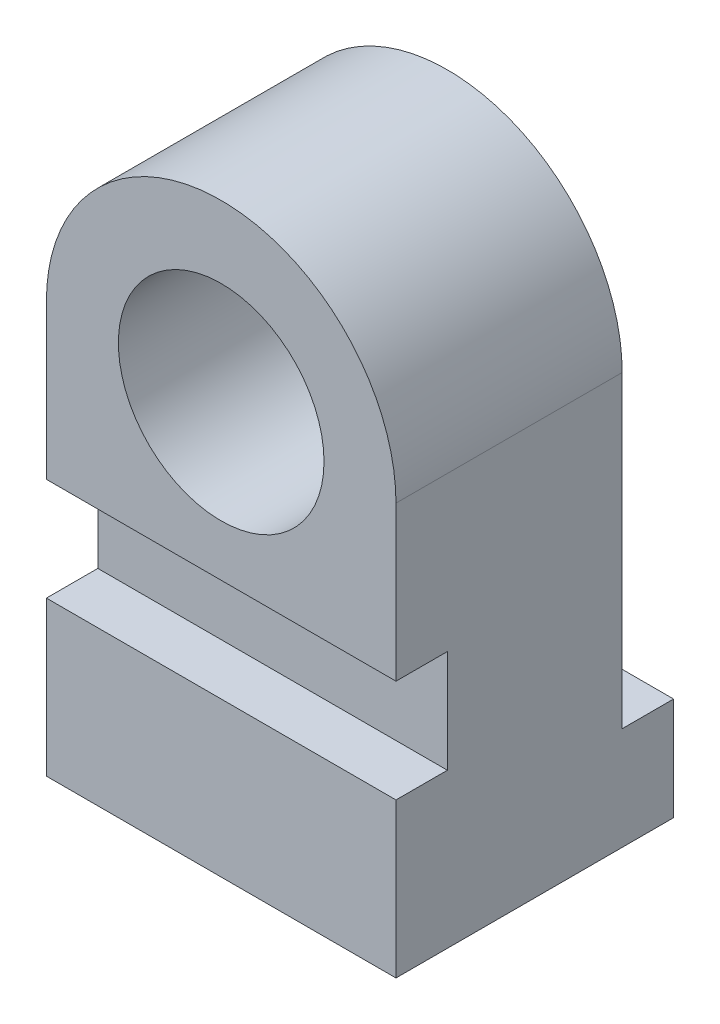
SolidWorks part; units mm, degrees
ref_plane "Front Plane" through (0, 0, 0) normal (0, 0, 1) x (1, 0, 0)
ref_plane "Top Plane" through (0, 0, 0) normal (0, 1, 0) x (1, 0, 0)
ref_plane "Right Plane" through (0, 0, 0) normal (1, 0, 0) x (0, 0, -1)
sketch "Sketch1" plane through (0, 0, 0) normal (0, 0, 1) x (1, 0, 0)
  line L0 (-17000, 0) -> (17000, 0)
  line L1 (0, 0) -> (0, 40000) construction
  line L2 (-24995.5692, 40000) -> (34311.1506, 40000) construction
  line L3 (-17000, 40000) -> (-17000, 0)
  line L4 (17000, 40000) -> (17000, 0)
  circle A0 centre (0, 40000) radius 10000
  arc A1 (17000, 40000) -> (-17000, 40000) centre (0, 40000) ccw
  dimension "D1" = 17000
  dimension "D2" = 20000
  dimension "D3" = 34000
  dimension "D4" = 17000
  dimension "D5" = 40000
extrude "Boss-Extrude1" add sketch "Sketch1" along normal blind 22000
sketch "Sketch2" plane through (0, 0, 22000) normal (0, 0, 1) x (1, 0, 0)
  line L0 (-17000, 40000) -> (-17000, 0) construction
  line L1 (-17000, 15000) -> (17000, 15000)
  line L2 (-17000, 15000) -> (-17000, 25000)
  line L3 (-17000, 25000) -> (17000, 25000)
  line L4 (17000, 15000) -> (17000, 25000)
  line L5 (17000, 0) -> (17000, 40000) construction
  dimension "D1" = 10000
  dimension "D2" = 15000
extrude "Cut-Extrude1" cut sketch "Sketch2" against normal blind 5000
sketch "Sketch3" plane through (0, 0, 0) normal (0, 0, -1) x (-1, 0, 0)
  line L0 (17000, 40000) -> (17000, 0) construction
  line L1 (-17000, 0) -> (17000, 0)
  line L2 (-17000, 0) -> (-17000, 10000)
  line L3 (-17000, 10000) -> (17000, 10000)
  line L4 (17000, 0) -> (17000, 10000)
  dimension "D1" = 10000
extrude "Boss-Extrude2" add sketch "Sketch3" along normal blind 5000
